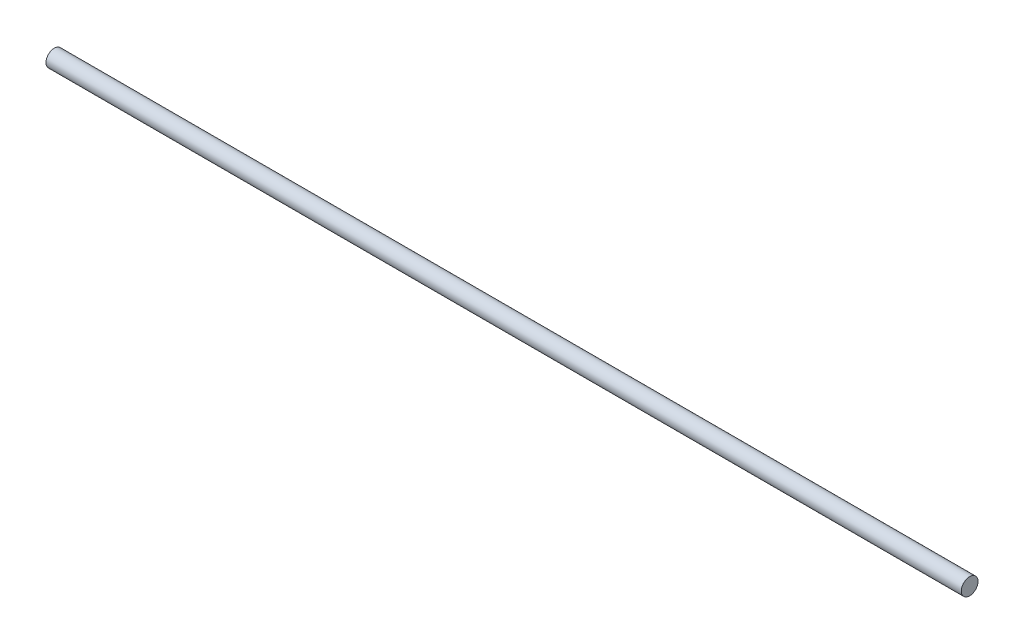
SolidWorks part; units mm, degrees
ref_plane "Alzado" through (0, 0, 0) normal (0, 0, 1) x (1, 0, 0)
ref_plane "Planta" through (0, 0, 0) normal (0, 1, 0) x (1, 0, 0)
ref_plane "Vista lateral" through (0, 0, 0) normal (1, 0, 0) x (0, 0, -1)
sketch "Croquis1" plane through (0, 0, 0) normal (1, 0, 0) x (0, 0, -1)
  circle A0 centre (0, 0) radius 2.5
  dimension "D1" = 5
extrude "Saliente-Extruir1" add sketch "Croquis1" along normal blind 274
